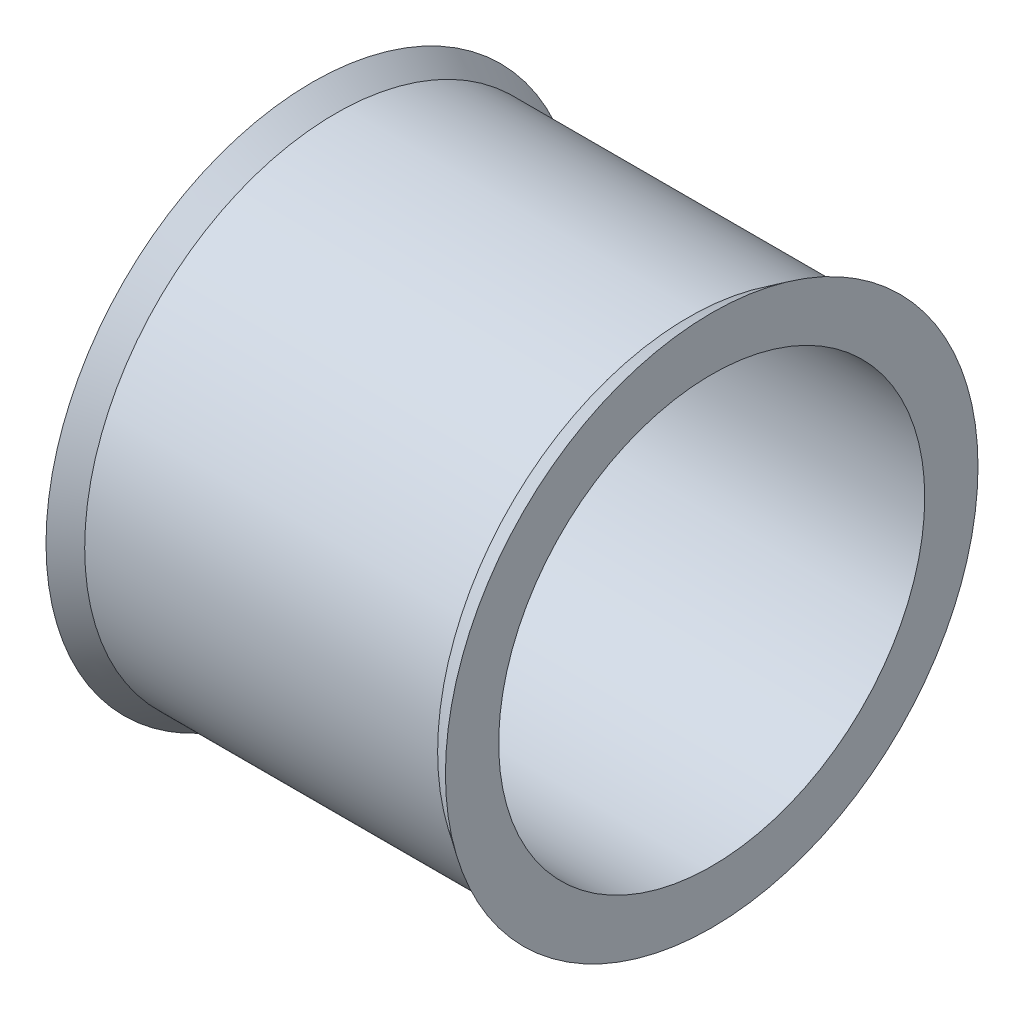
SolidWorks part; units mm, degrees
ref_plane "Front Plane" through (0, 0, 0) normal (0, 0, 1) x (1, 0, 0)
ref_plane "Top Plane" through (0, 0, 0) normal (0, 1, 0) x (1, 0, 0)
ref_plane "Right Plane" through (0, 0, 0) normal (1, 0, 0) x (0, 0, -1)
sketch "Sketch1" plane through (0, 0, 0) normal (0, 0, 1) x (1, 0, 0)
  line L0 (0, 0) -> (-136.4099, 0) construction
  line L1 (-7.3983, 80) -> (-157.3983, 80)
  line L2 (-157.3983, 80) -> (-157.3983, 100)
  line L3 (-157.3983, 100) -> (-148.6697, 94.1999)
  line L4 (-148.6697, 94.1999) -> (-16.127, 94.1999)
  line L5 (-16.127, 94.1999) -> (-7.3983, 100)
  line L6 (-7.3983, 100) -> (-7.3983, 80)
  dimension "D1" = 150
  dimension "D2" = 200
  dimension "D3" = 20
  dimension "D4" = 10.48
  dimension "D5" = 10.48
revolve "Revolve1" add sketch "Sketch1" angle 360 about L0
